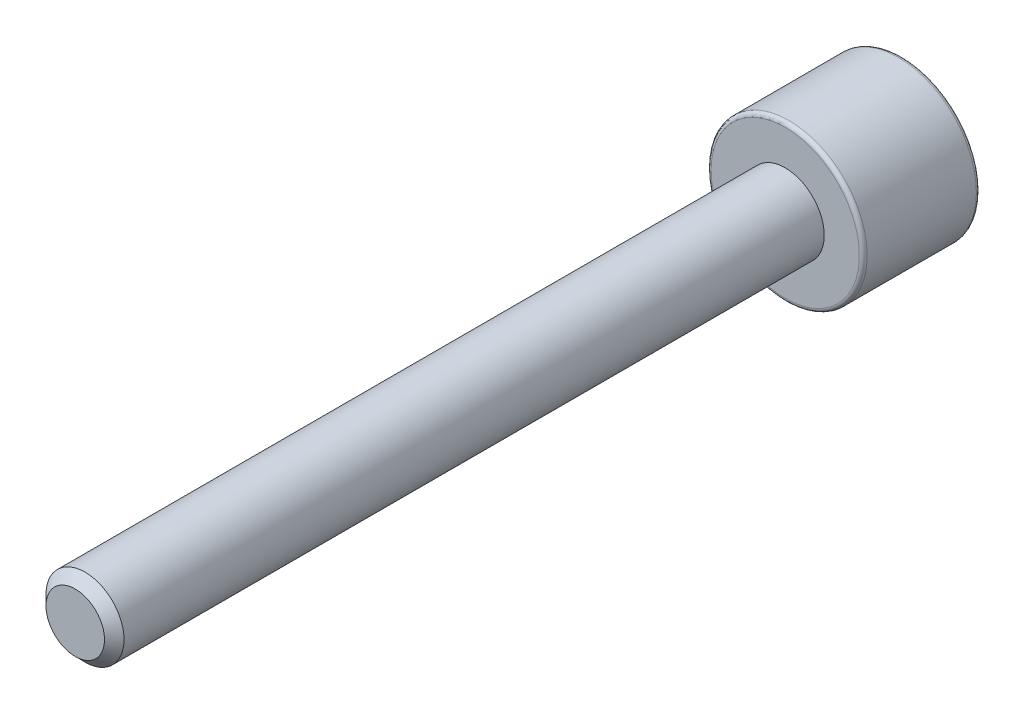
SolidWorks part; units mm, degrees
material "AISI 4140 Steel, quenched & tempered"
ref_plane "Front Plane" through (0, 0, 0) normal (1, 0, 0) x (0, 1, 0)
ref_plane "Top Plane" through (0, 0, 0) normal (0, 0, 1) x (0, 1, 0)
ref_plane "Right Plane" through (0, 0, 0) normal (0, 1, 0) x (-1, 0, 0)
sketch "Sketch1" plane through (0, 0, 0) normal (1, 0, 0) x (0, 1, 0)
  line L0 (0, 38.5484) -> (0, -38.1729) construction
  line L1 (0, 36.4) -> (2, 36.4)
  line L2 (2, 36.4) -> (2, 0)
  line L3 (2, 0) -> (4, 0)
  line L4 (4, 0) -> (4, -6)
  line L5 (4, -6) -> (0, -6)
  line L6 (0, -6) -> (0, 36.4)
  line L7 (-2.8767, 0) -> (6.4293, 0) construction
  dimension "D1" = 36.4
  dimension "D2" = 4
  dimension "D3" = 8
  dimension "D4" = 6
revolve "Revolve1" add sketch "Sketch1" angle 360 about L0
chamfer "Chamfer1" distance 0.5 angle 45 1 edges at (2, 0, 36.4)
fillet "Fillet1" radius 0.2 2 edges at (4, 0, -6) (4, 0, 0)
sketch "Sketch2" plane through (0, 0, -6) normal (0, 0, -1) x (1, 0, 0)
  line L0 (0, 1.9088) -> (0, -1.2909) construction
  line L1 (-2.0853, 0) -> (2.6481, 0) construction
  line L3 (0, -3) -> (2.5981, -1.5)
  line L4 (2.5981, -1.5) -> (2.5981, 1.5)
  line L5 (2.5981, 1.5) -> (0, 3)
  line L6 (0, 3) -> (-2.5981, 1.5)
  line L7 (-2.5981, 1.5) -> (-2.5981, -1.5)
  line L8 (-2.5981, -1.5) -> (0, -3)
  circle A0 centre (0, 0) radius 2.5981 construction
  dimension "D1" = 6
extrude "Cut-Extrude1" cut sketch "Sketch2" against normal blind 5 and the other way through all
fillet "Fillet2" radius 0.2 18 edges at (1.299, 2.25, -1) (2.5981, 0, -1) (1.299, -2.25, -1) (-1.299, -2.25, -1) (-1.299, 2.25, -1) (-2.5981, 0, -1) (1.299, 2.25, -6) (2.5981, 0, -6) (1.299, -2.25, -6) (-1.299, 2.25, -6) (-2.5981, 0, -6) (-1.299, -2.25, -6) (0, 3, -3.5) (2.5981, 1.5, -3.5) (2.5981, -1.5, -3.5) (-2.5981, 1.5, -3.5) (0, -3, -3.5) (-2.5981, -1.5, -3.5)
